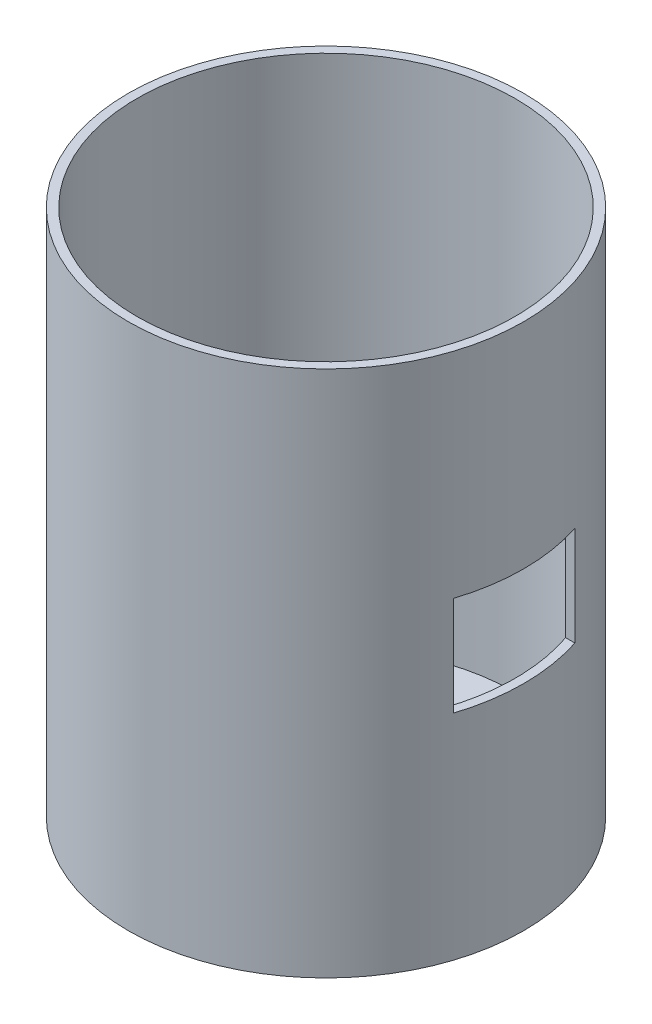
SolidWorks part; units mm, degrees
ref_plane "Front Plane" through (0, 0, 0) normal (0, 0, 1) x (1, 0, 0)
ref_plane "Top Plane" through (0, 0, 0) normal (0, 1, 0) x (1, 0, 0)
ref_plane "Right Plane" through (0, 0, 0) normal (1, 0, 0) x (0, 0, -1)
other "Configuration Table"
sketch "Sketch1" plane through (0, 0, 0) normal (0, 1, 0) x (1, 0, 0)
  circle A0 centre (0, 0) radius 45
  dimension "D1" = 90
extrude "Jar_Body" add sketch "Sketch1" along normal blind 120
sketch "Sketch2" plane through (0, 0, 0) normal (0, 1, 0) x (1, 0, 0)
  circle A0 centre (0, 0) radius 43
  dimension "D1" = 86
extrude "Jar_Inside" cut sketch "Sketch2" against normal blind 117 from offset 120
sketch "Sketch3" plane through (0, 0, 0) normal (1, 0, 0) x (0, 0, -1)
  line L0 (-13.8, 48.7) -> (13.8, 48.7)
  line L1 (13.8, 48.7) -> (13.8, 71.3)
  line L2 (13.8, 71.3) -> (-13.8, 71.3)
  line L3 (-13.8, 71.3) -> (-13.8, 48.7)
extrude "Turbidity_Hole" cut sketch "Sketch3" along normal blind 10 from offset 40
equation "\"Jar_OD\"= 90  'ASSUMED - Part G fallback - jar outer diameter"
equation "\"Jar_H\"= 120  'ASSUMED - Part G fallback - jar height"
equation "\"Pump_L\"= 45  'ASSUMED - Part G fallback"
equation "\"Pump_W\"= 24  'ASSUMED - Part G fallback"
equation "\"Pump_H\"= 33  'ASSUMED - Part G fallback"
equation "\"Pump_Outlet_OD\"= 7.5  'ASSUMED - Part G fallback"
equation "\"Tube_OD\"= 8  'ASSUMED - Part G fallback"
equation "\"Tube_ID\"= 6  'ASSUMED - Part G fallback"
equation "\"TDS_Body_Dia\"= 12  'ASSUMED - Part G fallback"
equation "\"TDS_Wet_Len\"= 45  'ASSUMED - Part G fallback - length in water"
equation "\"DS_Tube_Dia\"= 6  'ASSUMED - Part G fallback"
equation "\"DS_Tube_Len\"= 50  'ASSUMED - Part G fallback"
equation "\"ORP_Body_Dia\"= 12  'ASSUMED - Part G fallback"
equation "\"ORP_Body_Len\"= 150  'ASSUMED - Part G fallback"
equation "\"ORP_Cap_Dia\"= 16  'ASSUMED - Part G fallback"
equation "\"Turb_W\"= 33  'ASSUMED - Part G fallback - head width"
equation "\"Turb_D\"= 28  'ASSUMED - Part G fallback - head depth"
equation "\"Turb_H\"= 30  'ASSUMED - Part G fallback - head height"
equation "\"Turb_Slot_W\"= 10  'ASSUMED - Part G fallback - slot width"
equation "\"Flow_L\"= 62  'ASSUMED - Part G fallback YF-S201"
equation "\"Flow_W\"= 36  'ASSUMED - Part G fallback"
equation "\"Flow_H\"= 35  'ASSUMED - Part G fallback"
equation "\"Thread_G12_OD\"= 20.955  'ASSUMED - Part G fallback thread G1/2 (major diameter)"
equation "\"Valve_L\"= 75  'ASSUMED - Part G fallback"
equation "\"Valve_W\"= 45  'ASSUMED - Part G fallback"
equation "\"Valve_H\"= 60  'ASSUMED - Part G fallback"
equation "\"Tee_L\"= 40  'ASSUMED - Part G fallback - overall length"
equation "\"Tee_Branch_L\"= 25  'ASSUMED - Part G fallback"
equation "\"Tee_OD\"= 12  'ASSUMED - Part G fallback"
equation "\"LED_Board_L\"= 20  'ASSUMED - Part G fallback"
equation "\"LED_Board_W\"= 20  'ASSUMED - Part G fallback - LED at centre"
equation "\"GUVA_L\"= 20  'ASSUMED - Part G fallback"
equation "\"GUVA_W\"= 12  'ASSUMED - Part G fallback - sensor at centre"
equation "\"Reed_L\"= 27  'ASSUMED - Part G fallback MC-38 half"
equation "\"Reed_W\"= 14  'ASSUMED - Part G fallback"
equation "\"Reed_H\"= 8  'ASSUMED - Part G fallback"
equation "\"ESP_L\"= 51  'ASSUMED - Part G fallback"
equation "\"ESP_W\"= 28  'ASSUMED - Part G fallback"
equation "\"TFT_L\"= 58  'ASSUMED - Part G fallback - board"
equation "\"TFT_W\"= 35  'ASSUMED - Part G fallback - board"
equation "\"TFT_Win_L\"= 35  'ASSUMED - Part G fallback - visible window"
equation "\"TFT_Win_W\"= 28  'ASSUMED - Part G fallback - visible window"
equation "\"Relay_L\"= 50  'ASSUMED - Part G fallback"
equation "\"Relay_W\"= 26  'ASSUMED - Part G fallback"
equation "\"Relay_H\"= 19  'ASSUMED - Part G fallback"
equation "\"Mosfet_L\"= 34  'ASSUMED - Part G fallback"
equation "\"Mosfet_W\"= 17  'ASSUMED - Part G fallback"
equation "\"Mosfet_H\"= 12  'ASSUMED - Part G fallback"
equation "\"TDS_Board_L\"= 42  'ASSUMED - Part G fallback"
equation "\"TDS_Board_W\"= 32  'ASSUMED - Part G fallback"
equation "\"Turb_Board_L\"= 38  'ASSUMED - Part G fallback"
equation "\"Turb_Board_W\"= 28  'ASSUMED - Part G fallback"
equation "\"BNC_Thread_Dia\"= 9.5  'ASSUMED - Part G fallback"
equation "\"Plate_L\"= 420  'ASSUMED - Part G fallback"
equation "\"Plate_W\"= 297  'ASSUMED - Part G fallback"
equation "\"Plate_T\"= 6  'ASSUMED - Part G fallback"
equation "\"Booster_L\"= 150  'ASSUMED - Part G fallback - booster pump"
equation "\"Booster_W\"= 95  'ASSUMED - Part G fallback"
equation "\"Booster_H\"= 100  'ASSUMED - Part G fallback"
equation "\"PTube_OD\"= 6.35  'ASSUMED - Part G fallback - product tube 1/4 inch"
equation "\"Qz_Out\"= 12  'ASSUMED - Part G fallback - quartz channel outside square"
equation "\"Qz_Path\"= 10  'ASSUMED - Part G fallback - quartz channel inside light path"
equation "\"Qz_L\"= 40  'ASSUMED - Part G fallback - quartz channel length"
equation "\"LED860_Dia\"= 5  'ASSUMED - Part G fallback - 860 nm LED"
equation "\"BPW_L\"= 5.4  'ASSUMED - Part G fallback - BPW34"
equation "\"BPW_W\"= 4.3  'ASSUMED - Part G fallback - BPW34"
equation "\"Cart_Dia\"= 50  'ASSUMED - Part G fallback - sediment and pre-carbon cartridges"
equation "\"Cart_L\"= 255  'ASSUMED - Part G fallback"
equation "\"UF_Dia\"= 50  'ASSUMED - Part G fallback - UF cartridge"
equation "\"UF_L\"= 260  'ASSUMED - Part G fallback"
equation "\"RO_Dia\"= 62  'ASSUMED - Part G fallback - RO membrane housing"
equation "\"RO_L\"= 300  'ASSUMED - Part G fallback"
equation "\"UVC_Dia\"= 40  'ASSUMED - Part G fallback - UV-C chamber"
equation "\"UVC_L\"= 300  'ASSUMED - Part G fallback"
equation "\"Tank_W\"= 260  'ASSUMED - Part G fallback - storage tank"
equation "\"Tank_D\"= 160  'ASSUMED - Part G fallback"
equation "\"Tank_H\"= 300  'ASSUMED - Part G fallback"
equation "\"Cab_W\"= 400  'ASSUMED - Part G fallback - purifier cabinet"
equation "\"Cab_D\"= 270  'ASSUMED - Part G fallback"
equation "\"Cab_H\"= 560  'ASSUMED - Part G fallback"
equation "\"ORP_Board_L\"= 40  'ASSUMED - Part G fallback - ORP buffer board"
equation "\"ORP_Board_W\"= 30  'ASSUMED - Part G fallback"
equation "\"Opt_Board_L\"= 50  'ASSUMED - Part G fallback - optical front-end board"
equation "\"Opt_Board_W\"= 40  'ASSUMED - Part G fallback"
equation "\"Buck_L\"= 43  'ASSUMED - Part G fallback - 12 V to 5 V buck module"
equation "\"Buck_W\"= 21  'ASSUMED - Part G fallback"
equation "\"Buck_H\"= 14  'ASSUMED - Part G fallback"
equation "\"BB_L\"= 165  'ASSUMED - Part G fallback - breadboard (As_Built_R3 only)"
equation "\"BB_W\"= 55  'ASSUMED - Part G fallback"
equation "\"BB_H\"= 10  'ASSUMED - Part G fallback"
equation "\"Cuv_W\"= 12.5  'ASSUMED - old R3 cuvette (station suppressed in SS4)"
equation "\"Cuv_D\"= 12.5  'ASSUMED - old R3 cuvette (station suppressed in SS4)"
equation "\"Cuv_H\"= 45  'ASSUMED - old R3 cuvette (station suppressed in SS4)"
equation "\"Probe_Clr\"= 0.3  'DESIGN VALUE - Part C rule 3 - printed probe hole = diameter + 0.3"
equation "\"Label_H\"= 0.6  'DESIGN VALUE - Part D - raised label height"
equation "\"D1@Sketch1\" = \"Jar_OD\""
equation "\"D1@Jar_Body\" = \"Jar_H\""
